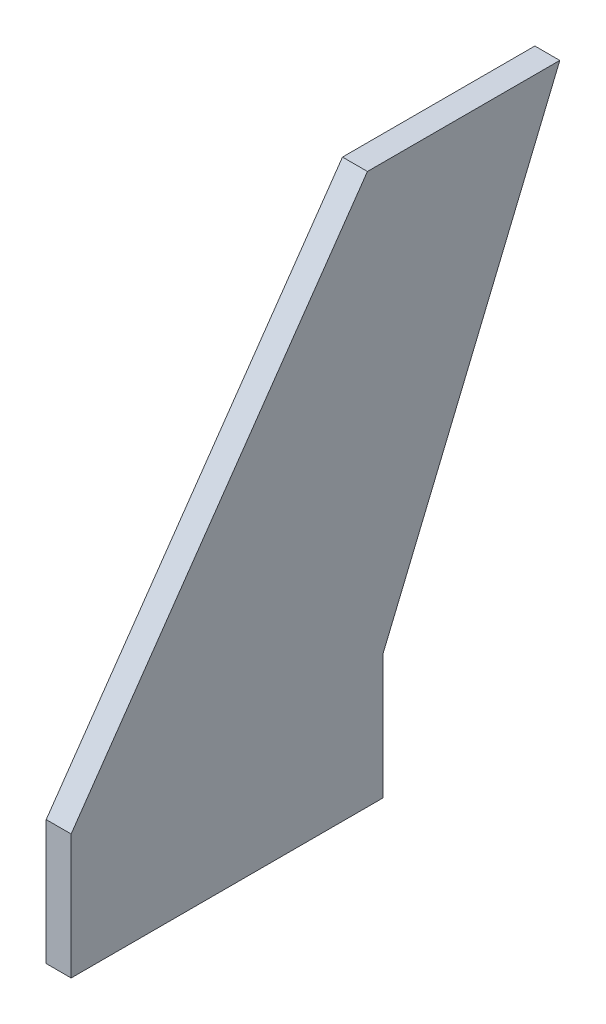
SolidWorks part; units mm, degrees
ref_plane "Alzado" through (0, 0, 0) normal (0, 0, 1) x (1, 0, 0)
ref_plane "Planta" through (0, 0, 0) normal (0, 1, 0) x (1, 0, 0)
ref_plane "Vista lateral" through (0, 0, 0) normal (1, 0, 0) x (0, 0, -1)
sketch "Croquis1" plane through (0, 0, 0) normal (1, 0, 0) x (0, 0, -1)
  line L0 (31.7775, 8.603) -> (79.2917, 76.856)
  line L1 (81.7775, 8.603) -> (81.7775, -11.397)
  line L2 (81.7775, -11.397) -> (31.7775, -11.397)
  line L3 (31.7775, -11.397) -> (31.7775, 8.603)
  line L4 (110.1413, 76.856) -> (79.2917, 76.856)
  line L6 (81.7775, 8.603) -> (110.1413, 76.856)
  dimension "D2" = 50
  dimension "D4" = 20
extrude "Saliente-Extruir1" add sketch "Croquis1" along normal blind 4
